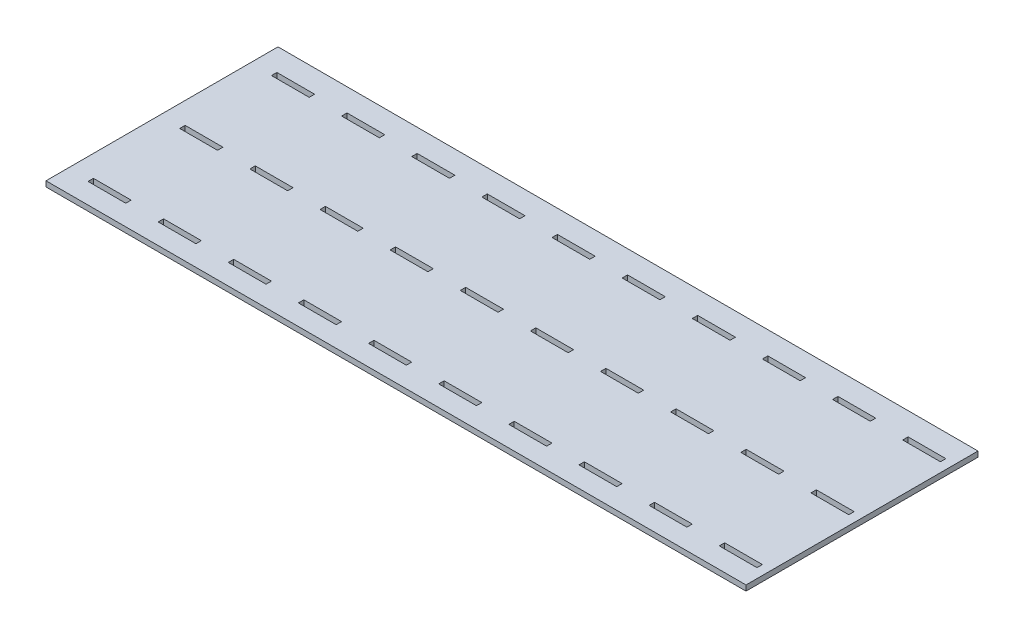
SolidWorks part; units mm, degrees
material "Balsa"
ref_plane "Front Plane" through (0, 0, 0) normal (0, 0, 1) x (1, 0, 0)
ref_plane "Top Plane" through (0, 0, 0) normal (0, 1, 0) x (1, 0, 0)
ref_plane "Right Plane" through (0, 0, 0) normal (1, 0, 0) x (0, 0, -1)
sketch "Sketch1" plane through (0, 0, 0) normal (0, 1, 0) x (1, 0, 0)
  line L0 (0, 0) -> (0, -273.05)
  line L1 (0, -273.05) -> (939.8, -273.05)
  line L2 (939.8, -273.05) -> (939.8, 0)
  line L3 (939.8, 0) -> (0, 0)
extrude "Boss-Extrude1" add sketch "Sketch1" along normal blind 6.35
sketch "Sketch2" plane through (0, 6.35, 0) normal (0, 1, 0) x (1, 0, 0)
  line L0 (25.4, -26.7387) -> (69.85, -26.7387)
  line L1 (69.85, -26.7387) -> (69.85, -33.0887)
  line L2 (69.85, -33.0887) -> (25.4, -33.0887)
  line L3 (25.4, -33.0887) -> (25.4, -26.7387)
  line L4 (107.95, -33.0887) -> (107.95, -26.7387)
  line L5 (107.95, -26.7387) -> (152.4, -26.7387)
  line L6 (152.4, -26.7387) -> (152.4, -33.0887)
  line L7 (152.4, -33.0887) -> (107.95, -33.0887)
  line L8 (190.5, -33.0887) -> (190.5, -26.7387)
  line L9 (190.5, -26.7387) -> (234.95, -26.7387)
  line L10 (234.95, -26.7387) -> (234.95, -33.0887)
  line L11 (234.95, -33.0887) -> (190.5, -33.0887)
  line L12 (273.05, -33.0887) -> (273.05, -26.7387)
  line L13 (273.05, -26.7387) -> (317.5, -26.7387)
  line L14 (317.5, -26.7387) -> (317.5, -33.0887)
  line L15 (317.5, -33.0887) -> (273.05, -33.0887)
  line L16 (355.6, -33.0887) -> (355.6, -26.7387)
  line L17 (355.6, -26.7387) -> (400.05, -26.7387)
  line L18 (400.05, -26.7387) -> (400.05, -33.0887)
  line L19 (400.05, -33.0887) -> (355.6, -33.0887)
  line L20 (438.15, -33.0887) -> (438.15, -26.7387)
  line L21 (438.15, -26.7387) -> (482.6, -26.7387)
  line L22 (482.6, -26.7387) -> (482.6, -33.0887)
  line L23 (482.6, -33.0887) -> (438.15, -33.0887)
  line L24 (520.7, -33.0887) -> (520.7, -26.7387)
  line L25 (520.7, -26.7387) -> (565.15, -26.7387)
  line L26 (565.15, -26.7387) -> (565.15, -33.0887)
  line L27 (565.15, -33.0887) -> (520.7, -33.0887)
  line L28 (603.25, -33.0887) -> (603.25, -26.7387)
  line L29 (603.25, -26.7387) -> (647.7, -26.7387)
  line L30 (647.7, -26.7387) -> (647.7, -33.0887)
  line L31 (647.7, -33.0887) -> (603.25, -33.0887)
  line L32 (685.8, -33.0887) -> (685.8, -26.7387)
  line L33 (685.8, -26.7387) -> (730.25, -26.7387)
  line L34 (730.25, -26.7387) -> (730.25, -33.0887)
  line L35 (730.25, -33.0887) -> (685.8, -33.0887)
  line L36 (768.35, -33.0887) -> (768.35, -26.7387)
  line L37 (768.35, -26.7387) -> (812.8, -26.7387)
  line L38 (812.8, -26.7387) -> (812.8, -33.0887)
  line L39 (812.8, -33.0887) -> (768.35, -33.0887)
  line L40 (107.95, -141.0387) -> (107.95, -134.6887)
  line L41 (107.95, -134.6887) -> (152.4, -134.6887)
  line L42 (152.4, -134.6887) -> (152.4, -141.0387)
  line L43 (152.4, -141.0387) -> (107.95, -141.0387)
  line L44 (190.5, -141.0387) -> (190.5, -134.6887)
  line L45 (190.5, -134.6887) -> (234.95, -134.6887)
  line L46 (234.95, -134.6887) -> (234.95, -141.0387)
  line L47 (234.95, -141.0387) -> (190.5, -141.0387)
  line L48 (273.05, -141.0387) -> (273.05, -134.6887)
  line L49 (273.05, -134.6887) -> (317.5, -134.6887)
  line L50 (317.5, -134.6887) -> (317.5, -141.0387)
  line L51 (317.5, -141.0387) -> (273.05, -141.0387)
  line L52 (355.6, -141.0387) -> (355.6, -134.6887)
  line L53 (355.6, -134.6887) -> (400.05, -134.6887)
  line L54 (400.05, -134.6887) -> (400.05, -141.0387)
  line L55 (400.05, -141.0387) -> (355.6, -141.0387)
  line L56 (438.15, -141.0387) -> (438.15, -134.6887)
  line L57 (438.15, -134.6887) -> (482.6, -134.6887)
  line L58 (482.6, -134.6887) -> (482.6, -141.0387)
  line L59 (482.6, -141.0387) -> (438.15, -141.0387)
  line L60 (520.7, -141.0387) -> (520.7, -134.6887)
  line L61 (520.7, -134.6887) -> (565.15, -134.6887)
  line L62 (565.15, -134.6887) -> (565.15, -141.0387)
  line L63 (565.15, -141.0387) -> (520.7, -141.0387)
  line L64 (603.25, -141.0387) -> (603.25, -134.6887)
  line L65 (603.25, -134.6887) -> (647.7, -134.6887)
  line L66 (647.7, -134.6887) -> (647.7, -141.0387)
  line L67 (647.7, -141.0387) -> (603.25, -141.0387)
  line L68 (685.8, -141.0387) -> (685.8, -134.6887)
  line L69 (685.8, -134.6887) -> (730.25, -134.6887)
  line L70 (730.25, -134.6887) -> (730.25, -141.0387)
  line L71 (730.25, -141.0387) -> (685.8, -141.0387)
  line L72 (768.35, -141.0387) -> (768.35, -134.6887)
  line L73 (768.35, -134.6887) -> (812.8, -134.6887)
  line L74 (812.8, -134.6887) -> (812.8, -141.0387)
  line L75 (812.8, -141.0387) -> (768.35, -141.0387)
  line L76 (107.95, -248.9887) -> (107.95, -242.6387)
  line L77 (107.95, -242.6387) -> (152.4, -242.6387)
  line L78 (152.4, -242.6387) -> (152.4, -248.9887)
  line L79 (152.4, -248.9887) -> (107.95, -248.9887)
  line L80 (190.5, -248.9887) -> (190.5, -242.6387)
  line L81 (190.5, -242.6387) -> (234.95, -242.6387)
  line L82 (234.95, -242.6387) -> (234.95, -248.9887)
  line L83 (234.95, -248.9887) -> (190.5, -248.9887)
  line L84 (273.05, -248.9887) -> (273.05, -242.6387)
  line L85 (273.05, -242.6387) -> (317.5, -242.6387)
  line L86 (317.5, -242.6387) -> (317.5, -248.9887)
  line L87 (317.5, -248.9887) -> (273.05, -248.9887)
  line L88 (355.6, -248.9887) -> (355.6, -242.6387)
  line L89 (355.6, -242.6387) -> (400.05, -242.6387)
  line L90 (400.05, -242.6387) -> (400.05, -248.9887)
  line L91 (400.05, -248.9887) -> (355.6, -248.9887)
  line L92 (438.15, -248.9887) -> (438.15, -242.6387)
  line L93 (438.15, -242.6387) -> (482.6, -242.6387)
  line L94 (482.6, -242.6387) -> (482.6, -248.9887)
  line L95 (482.6, -248.9887) -> (438.15, -248.9887)
  line L96 (520.7, -248.9887) -> (520.7, -242.6387)
  line L97 (520.7, -242.6387) -> (565.15, -242.6387)
  line L98 (565.15, -242.6387) -> (565.15, -248.9887)
  line L99 (565.15, -248.9887) -> (520.7, -248.9887)
  line L100 (603.25, -248.9887) -> (603.25, -242.6387)
  line L101 (603.25, -242.6387) -> (647.7, -242.6387)
  line L102 (647.7, -242.6387) -> (647.7, -248.9887)
  line L103 (647.7, -248.9887) -> (603.25, -248.9887)
  line L104 (685.8, -248.9887) -> (685.8, -242.6387)
  line L105 (685.8, -242.6387) -> (730.25, -242.6387)
  line L106 (730.25, -242.6387) -> (730.25, -248.9887)
  line L107 (730.25, -248.9887) -> (685.8, -248.9887)
  line L108 (768.35, -248.9887) -> (768.35, -242.6387)
  line L109 (768.35, -242.6387) -> (812.8, -242.6387)
  line L110 (812.8, -242.6387) -> (812.8, -248.9887)
  line L111 (812.8, -248.9887) -> (768.35, -248.9887)
  line L112 (25.4, -141.0387) -> (25.4, -134.6887)
  line L113 (25.4, -134.6887) -> (69.85, -134.6887)
  line L114 (69.85, -134.6887) -> (69.85, -141.0387)
  line L115 (69.85, -141.0387) -> (25.4, -141.0387)
  line L116 (25.4, -248.9887) -> (25.4, -242.6387)
  line L117 (25.4, -242.6387) -> (69.85, -242.6387)
  line L118 (69.85, -242.6387) -> (69.85, -248.9887)
  line L119 (69.85, -248.9887) -> (25.4, -248.9887)
  line L120 (939.8, -134.6887) -> (850.9, -134.6887)
  line L121 (850.9, -134.6887) -> (850.9, -141.0387)
  line L122 (850.9, -141.0387) -> (939.8, -141.0387)
  line L123 (850.9, -26.7387) -> (850.9, -33.0887)
  line L124 (850.9, -33.0887) -> (939.8, -33.0887)
  line L125 (939.8, -273.05) -> (939.8, 0) construction
  line L126 (939.8, -33.0887) -> (939.8, -26.7387)
  line L127 (939.8, -26.7387) -> (850.9, -26.7387)
  line L128 (939.8, -141.0387) -> (939.8, -134.6887)
  line L129 (939.8, -242.6387) -> (850.9, -242.6387)
  line L130 (850.9, -242.6387) -> (850.9, -248.9887)
  line L131 (850.9, -248.9887) -> (939.8, -248.9887)
  line L132 (939.8, -248.9887) -> (939.8, -242.6387)
  dimension "D1" = 10
  dimension "D3" = 3
  dimension "D2" = 3
extrude "Cut-Extrude1" cut sketch "Sketch2" against normal through all both and the other way through all
sketch "Sketch3" plane through (0, 0, 0) normal (0, -1, 0) x (1, 0, 0)
  line L0 (939.8, 0) -> (0, 0) construction
  line L1 (939.8, 273.05) -> (823.923, 273.05)
  line L2 (939.8, 273.05) -> (939.8, 0)
  line L3 (939.8, 0) -> (823.923, 0)
  line L4 (823.923, 273.05) -> (823.923, 0)
extrude "Cut-Extrude2" cut sketch "Sketch3" against normal up to surface (6.35 mm away) up to face at (708.025, 6.35, 29.9137)
